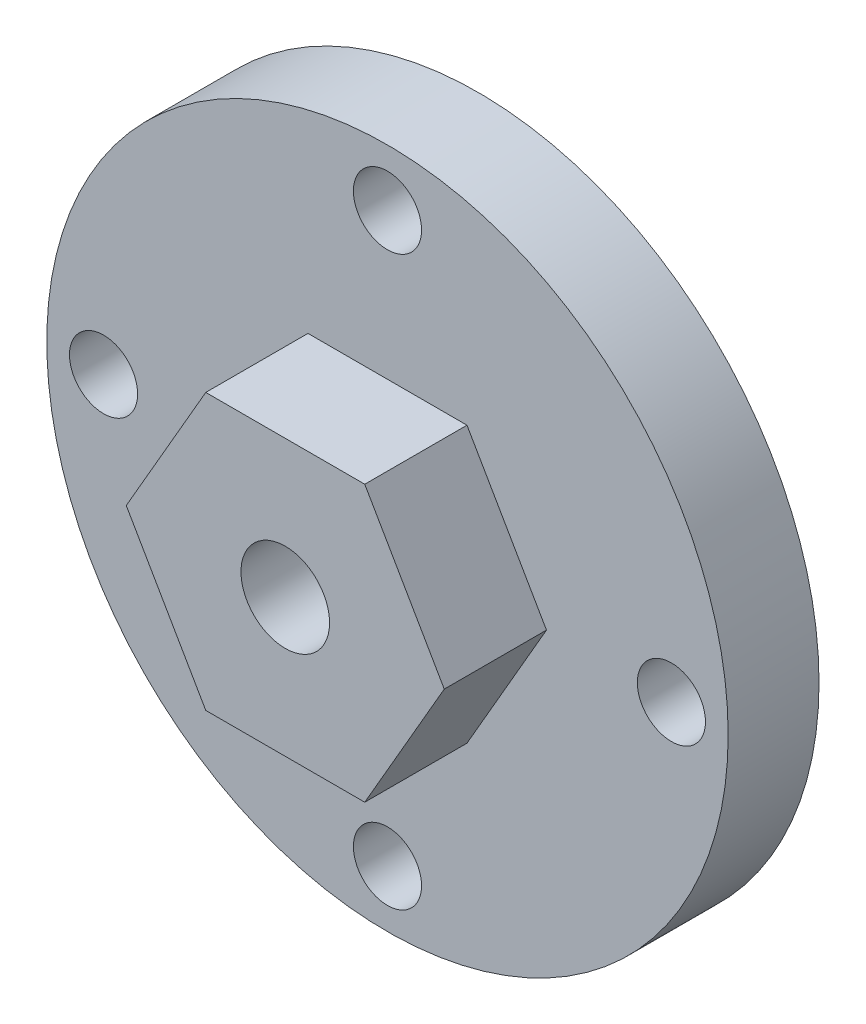
SolidWorks part; units mm, degrees
ref_plane "前视基准面" through (0, 0, 0) normal (0, 0, 1) x (1, 0, 0)
ref_plane "上视基准面" through (0, 0, 0) normal (0, 1, 0) x (1, 0, 0)
ref_plane "右视基准面" through (0, 0, 0) normal (1, 0, 0) x (0, 0, -1)
other "Configuration Table"
sketch "草图1" plane through (0, 0, 0) normal (0, 0, 1) x (1, 0, 0)
  circle A0 centre (0, 0) radius 15
  dimension "D1" = 30
extrude "凸台-拉伸1" add sketch "草图1" along normal blind 4
sketch "草图2" plane through (0, 0, 4) normal (0, 0, 1) x (1, 0, 0)
  line L0 (0, 0) -> (3.5, 6.0622) construction
  line L1 (3.5, 6.0622) -> (-3.5, 6.0622)
  line L2 (-3.5, 6.0622) -> (0, 0) construction
  line L3 (3.5, 6.0622) -> (0, 0) construction
  line L4 (0, 0) -> (7, 0) construction
  line L5 (7, 0) -> (3.5, 6.0622)
  line L6 (7, 0) -> (0, 0) construction
  line L7 (0, 0) -> (3.5, -6.0622) construction
  line L8 (3.5, -6.0622) -> (7, 0)
  line L9 (3.5, -6.0622) -> (0, 0) construction
  line L10 (0, 0) -> (-3.5, -6.0622) construction
  line L11 (-3.5, -6.0622) -> (3.5, -6.0622)
  line L12 (-3.5, -6.0622) -> (0, 0) construction
  line L13 (0, 0) -> (-7, 0) construction
  line L14 (-7, 0) -> (-3.5, -6.0622)
  line L15 (-7, 0) -> (0, 0) construction
  line L16 (0, 0) -> (-3.5, 6.0622) construction
  line L17 (-3.5, 6.0622) -> (-7, 0)
  point P17 (0, 0)
  dimension "D1" = 7
  dimension "D2" = 6
extrude "凸台-拉伸2" add sketch "草图2" along normal blind 4.5
sketch "草图3" plane through (0, 0, 8.5) normal (0, 0, 1) x (1, 0, 0)
  circle A0 centre (0, 0) radius 1.95
  dimension "D1" = 3.9
extrude "切除-拉伸1" cut sketch "草图3" against normal through all
sketch "草图6" plane through (0, 0, 0) normal (0, 0, -1) x (-1, 0, 0)
  line L0 (0, 0) -> (-12.5, 0) construction
  circle A2 centre (0, 0) radius 12.5 construction
  circle A3 centre (0, 12.5) radius 1.5
  circle A4 centre (12.5, 0) radius 1.5
  circle A5 centre (0, -12.5) radius 1.5
  circle A6 centre (-12.5, 0) radius 1.5
  point P14 (0, 0)
  dimension "D1" = 25
  dimension "D2" = 3
  dimension "D4" = 12.5
  dimension "D3" = 4
extrude "切除-拉伸2" cut sketch "草图6" against normal through all contours A3 | A4 | A5 | A6
